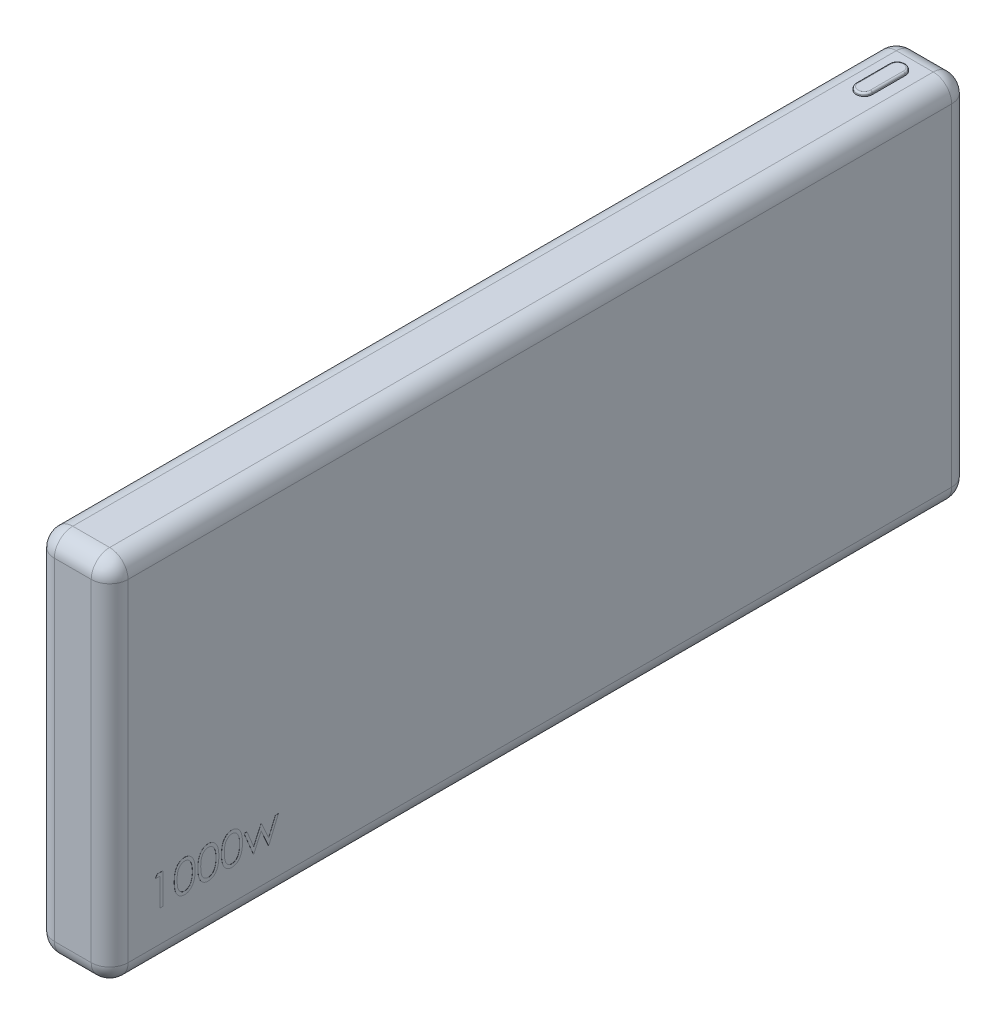
SolidWorks part; units mm, degrees
ref_plane "Front Plane" through (0, 0, 0) normal (0, 0, 1) x (1, 0, 0)
ref_plane "Top Plane" through (0, 0, 0) normal (0, 1, 0) x (1, 0, 0)
ref_plane "Right Plane" through (0, 0, 0) normal (1, 0, 0) x (0, 0, -1)
sketch "Sketch2" plane through (0, 0, 0) normal (1, 0, 0) x (0, 0, -1)
  line L1 (-7, 3) -> (7, 3)
  line L2 (-7, 3) -> (-7, -3)
  line L3 (-7, -3) -> (7, -3)
  line L4 (7, 3) -> (7, -3)
  line L5 (-7, 3) -> (7, -3) construction
  line L6 (-7, -3) -> (7, 3) construction
  point P0 (0, 0)
  dimension "D1" = 6
  dimension "D2" = 14
extrude "Boss-Extrude1" add sketch "Sketch2" along normal blind 1.2
fillet "Fillet1" radius 0.3 12 edges at (1.2, -3, 0) (0, -3, 0) (1.2, 0, 7) (0.6, -3, 7) (0, 0, 7) (1.2, 3, 0) (0.6, 3, 7) (0, 3, 0) (0.6, -3, -7) (1.2, 0, -7) (0.6, 3, -7) (0, 0, -7)
sketch "Sketch3" plane through (0, 0, -7) normal (0, 0, -1) x (-1, 0, 0)
  line L0 (-0.6, 2.4) -> (-0.6, 2.1) construction
  line L1 (-0.45, 2.4) -> (-0.45, 2.1)
  line L2 (-0.75, 2.4) -> (-0.75, 2.1)
  line L3 (-0.9, 2.7) -> (-0.9, -2.7) construction
  line L4 (-0.3, -2.7) -> (-0.3, 2.7) construction
  line L5 (-0.3, 2.7) -> (-0.9, 2.7) construction
  line L6 (-0.6, 1.4) -> (-0.6, 1.1) construction
  line L7 (-0.45, 1.4) -> (-0.45, 1.1)
  line L8 (-0.75, 1.4) -> (-0.75, 1.1)
  arc A0 (-0.45, 2.4) -> (-0.75, 2.4) centre (-0.6, 2.4) ccw
  arc A1 (-0.75, 2.1) -> (-0.45, 2.1) centre (-0.6, 2.1) ccw
  arc A2 (-0.45, 1.4) -> (-0.75, 1.4) centre (-0.6, 1.4) ccw
  arc A3 (-0.75, 1.1) -> (-0.45, 1.1) centre (-0.6, 1.1) ccw
  point P2 (-0.6, 2.25)
  point P15 (-0.6, 1.25)
  dimension "D7" = 0.15
  dimension "D1" = 0.3
  dimension "D2" = 0.3
  dimension "D3" = 0.15
  dimension "D4" = 0.15
  dimension "D5" = 0.3
  dimension "D6" = 1
  dimension "D8" = 0.15
  dimension "D9" = 0.3
extrude "Cut-Extrude1" cut sketch "Sketch3" against normal blind 0.6
sketch "Sketch4" plane through (0, 0, -6.4) normal (0, 0, -1) x (-1, 0, 0)
  line L6 (-0.66, 2.4) -> (-0.66, 2.1)
  line L7 (-0.54, 2.1) -> (-0.54, 2.4)
  line L8 (-0.66, 2.4) -> (-0.66, 2.1)
  line L9 (-0.54, 2.1) -> (-0.54, 2.4)
  line L12 (-0.66, 1.4) -> (-0.66, 1.1)
  line L13 (-0.54, 1.1) -> (-0.54, 1.4)
  line L14 (-0.66, 1.4) -> (-0.66, 1.1)
  line L15 (-0.54, 1.1) -> (-0.54, 1.4)
  arc A6 (-0.54, 2.4) -> (-0.66, 2.4) centre (-0.6, 2.4) ccw
  arc A7 (-0.66, 2.1) -> (-0.54, 2.1) centre (-0.6, 2.1) ccw
  arc A8 (-0.54, 2.4) -> (-0.66, 2.4) centre (-0.6, 2.4) ccw
  arc A9 (-0.66, 2.1) -> (-0.54, 2.1) centre (-0.6, 2.1) ccw
  arc A12 (-0.54, 1.4) -> (-0.66, 1.4) centre (-0.6, 1.4) ccw
  arc A13 (-0.66, 1.1) -> (-0.54, 1.1) centre (-0.6, 1.1) ccw
  arc A14 (-0.54, 1.4) -> (-0.66, 1.4) centre (-0.6, 1.4) ccw
  arc A15 (-0.66, 1.1) -> (-0.54, 1.1) centre (-0.6, 1.1) ccw
  dimension "D1" = 0.09
  dimension "D2" = 0.09
extrude "Boss-Extrude2" add sketch "Sketch4" along normal blind 0.4
sketch "Sketch5" plane through (1.2, 0, 0) normal (1, 0, 0) x (0, 0, -1)
  text T0 "1000w" font "Century Gothic" height 0.5
extrude "Boss-Extrude3" add sketch "Sketch5" along normal blind 0.002
sketch "Sketch6" plane through (0, 0, -7) normal (0, 0, -1) x (-1, 0, 0)
  line L1 (-0.8, 0.49) -> (-0.4, 0.49)
  line L2 (-0.8, 0.49) -> (-0.8, -0.41)
  line L3 (-0.8, -0.41) -> (-0.4, -0.41)
  line L4 (-0.4, 0.49) -> (-0.4, -0.41)
  line L5 (-0.8, 0.49) -> (-0.4, -0.41) construction
  line L6 (-0.8, -0.41) -> (-0.4, 0.49) construction
  line L7 (-0.8, -1.01) -> (-0.4, -1.01)
  line L8 (-0.8, -1.01) -> (-0.8, -1.91)
  line L9 (-0.8, -1.91) -> (-0.4, -1.91)
  line L10 (-0.4, -1.01) -> (-0.4, -1.91)
  line L11 (-0.8, -1.01) -> (-0.4, -1.91) construction
  line L12 (-0.8, -1.91) -> (-0.4, -1.01) construction
  line L16 (-0.9, 2.7) -> (-0.9, -2.7) construction
  line L17 (-0.3, -2.7) -> (-0.3, 2.7) construction
  arc A0 (-0.66, 1.1) -> (-0.54, 1.1) centre (-0.6, 1.1) ccw construction
  point P0 (-0.6, 0.04)
  point P5 (-0.6, -1.46)
  point P13 (-0.6, 1.04)
  point P16 (-0.6136, 0.0676)
  dimension "D1" = 1
  dimension "D2" = 1.5
  dimension "D3" = 0.4
  dimension "D4" = 0.9
  dimension "D5" = 0.1
  dimension "D6" = 0.1
  dimension "D7" = 0.1
extrude "Cut-Extrude2" cut sketch "Sketch6" against normal blind 0.9
sketch "Sketch7" plane through (0, 0, -6.1) normal (0, 0, -1) x (-1, 0, 0)
  line L0 (-0.8, -0.41) -> (-0.4, -0.41) construction
  line L1 (-0.5, 0.39) -> (-0.6, 0.39)
  line L2 (-0.5, 0.39) -> (-0.5, -0.31)
  line L3 (-0.5, -0.31) -> (-0.6, -0.31)
  line L4 (-0.6, 0.39) -> (-0.6, -0.31)
  line L5 (-0.4, 0.49) -> (-0.8, 0.49) construction
  line L6 (-0.4, -0.41) -> (-0.4, 0.49) construction
  line L7 (-0.5, -1.81) -> (-0.6, -1.81)
  line L8 (-0.6, -1.11) -> (-0.6, -1.81)
  line L9 (-0.5, -1.11) -> (-0.5, -1.81)
  line L10 (-0.5, -1.11) -> (-0.6, -1.11)
  line L11 (-0.4, -1.91) -> (-0.4, -1.01) construction
  line L12 (-0.4, -1.01) -> (-0.8, -1.01) construction
  line L13 (-0.8, -1.91) -> (-0.4, -1.91) construction
  point P18 (-0.55, -1.81)
  dimension "D1" = 0.1
  dimension "D2" = 0.1
  dimension "D3" = 0.1
  dimension "D4" = 0.1
  dimension "D5" = 0.1
  dimension "D6" = 0.1
  dimension "D7" = 0.1
  dimension "D8" = 0.1
extrude "Boss-Extrude4" add sketch "Sketch7" along normal blind 0.7
sketch "Sketch8" plane through (0, 3, 0) normal (0, 1, 0) x (1, 0, 0)
  line L0 (0.5934, 6.4203) -> (0.5934, 5.8846) construction
  line L1 (0.7235, 6.4203) -> (0.7235, 5.8846)
  line L2 (0.4633, 6.4203) -> (0.4633, 5.8846)
  arc A0 (0.7235, 6.4203) -> (0.4633, 6.4203) centre (0.5934, 6.4203) ccw
  arc A1 (0.4633, 5.8846) -> (0.7235, 5.8846) centre (0.5934, 5.8846) ccw
  point P2 (0.5934, 6.1525)
extrude "Boss-Extrude5" add sketch "Sketch8" along normal blind 0.05
fillet "Fillet2" radius 0.03 4 edges at (0.5934, 3.05, -5.7545) (0.4633, 3.05, -6.1525) (0.5934, 3.05, -6.5505) (0.7235, 3.05, -6.1525)
